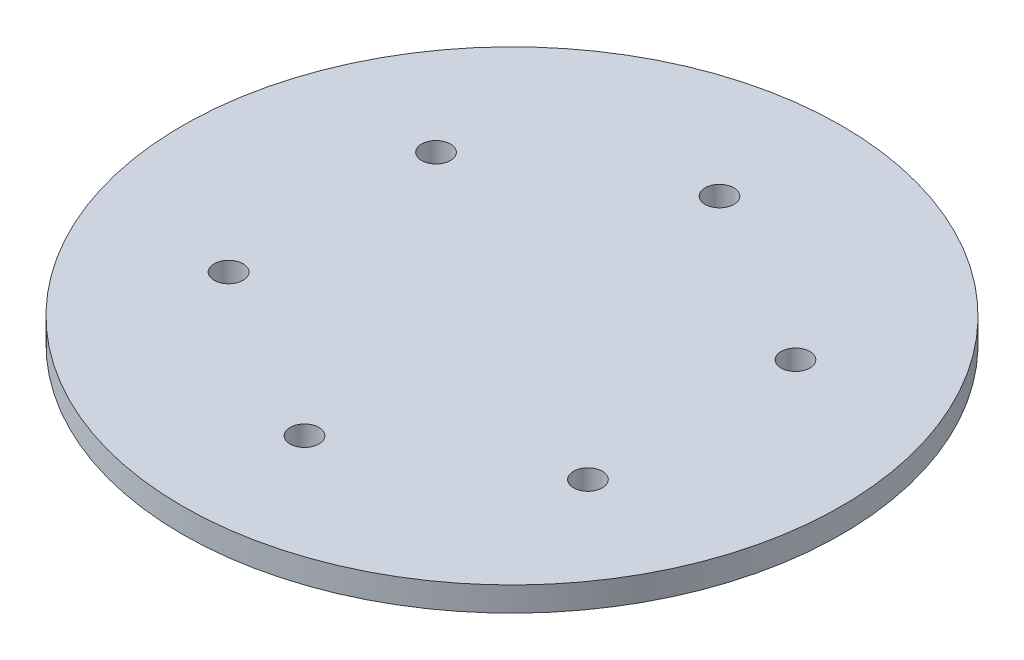
SolidWorks part; units mm, degrees
ref_plane "Front Plane" through (0, 0, 0) normal (0, 0, 1) x (1, 0, 0)
ref_plane "Top Plane" through (0, 0, 0) normal (0, 1, 0) x (1, 0, 0)
ref_plane "Right Plane" through (0, 0, 0) normal (1, 0, 0) x (0, 0, -1)
sketch "Sketch1" plane through (0, 0, 0) normal (0, 1, 0) x (1, 0, 0)
  circle A0 centre (0, 0) radius 67.5
  dimension "D1" = 135
extrude "Boss-Extrude1" add sketch "Sketch1" along normal mid plane 5
sketch "Sketch2" plane through (0, 2.5, 0) normal (0, 1, 0) x (1, 0, 0)
  circle A0 centre (0, 0) radius 42.5
  circle A1 centre (0, 42.5) radius 2.95
  circle A2 centre (36.8061, 21.25) radius 2.95
  circle A3 centre (36.8061, -21.25) radius 2.95
  circle A4 centre (0, -42.5) radius 2.95
  circle A5 centre (-36.8061, -21.25) radius 2.95
  circle A6 centre (-36.8061, 21.25) radius 2.95
  point P17 (0, 0)
  dimension "D1" = 5.9
  dimension "D3" = 85
  dimension "D2" = 6
extrude "Cut-Extrude1" cut sketch "Sketch2" against normal blind 5 contours A1 | A2 | A3 | A4 | A5 | A6
